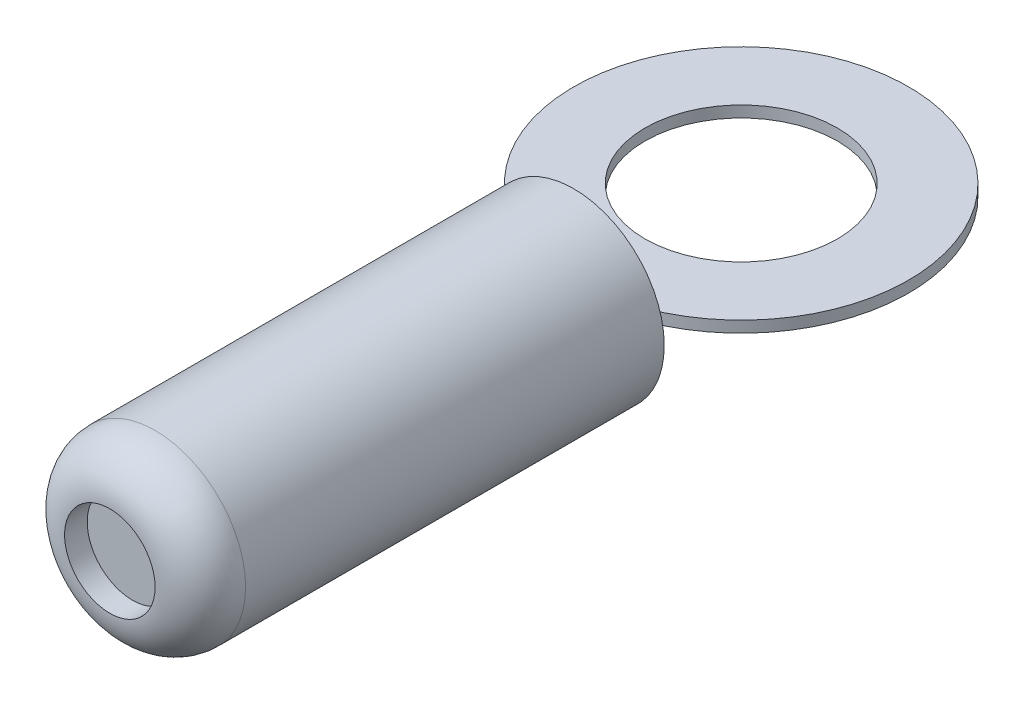
SolidWorks part; units mm, degrees
ref_plane "正面" through (0, 0, 0) normal (0, 0, 1) x (1, 0, 0)
ref_plane "平面" through (0, 0, 0) normal (0, 1, 0) x (1, 0, 0)
ref_plane "右側面" through (0, 0, 0) normal (1, 0, 0) x (0, 0, -1)
sketch "ｽｹｯﾁ8" plane through (0, 0, 0) normal (0, 0, 1) x (1, 0, 0)
  circle A0 centre (0, 0) radius 4
  dimension "D1" = 8
extrude "ﾎﾞｽ - 押し出し4" add sketch "ｽｹｯﾁ8" along normal blind 20.5
sketch "ｽｹｯﾁ10" plane through (0, 0, 0) normal (0, 1, 0) x (1, 0, 0)
  line L0 (0, 0) -> (0, 7.4) construction
  circle A0 centre (0, 7.4) radius 7.4
  circle A1 centre (0, 7.4) radius 4.25
  dimension "D2" = 8.5
  dimension "D1" = 7.4
extrude "ﾎﾞｽ - 押し出し5" add sketch "ｽｹｯﾁ10" along normal blind 0.5 separate body
fillet "ﾌｨﾚｯﾄ1" radius 2 1 edges at (4, 0, 20.5)
sketch "ｽｹｯﾁ11" plane through (0, 0, 20.5) normal (0, 0, 1) x (1, 0, 0)
  circle A0 centre (0, 0) radius 2
extrude "ｶｯﾄ - 押し出し1" cut sketch "ｽｹｯﾁ11" against normal blind 1
